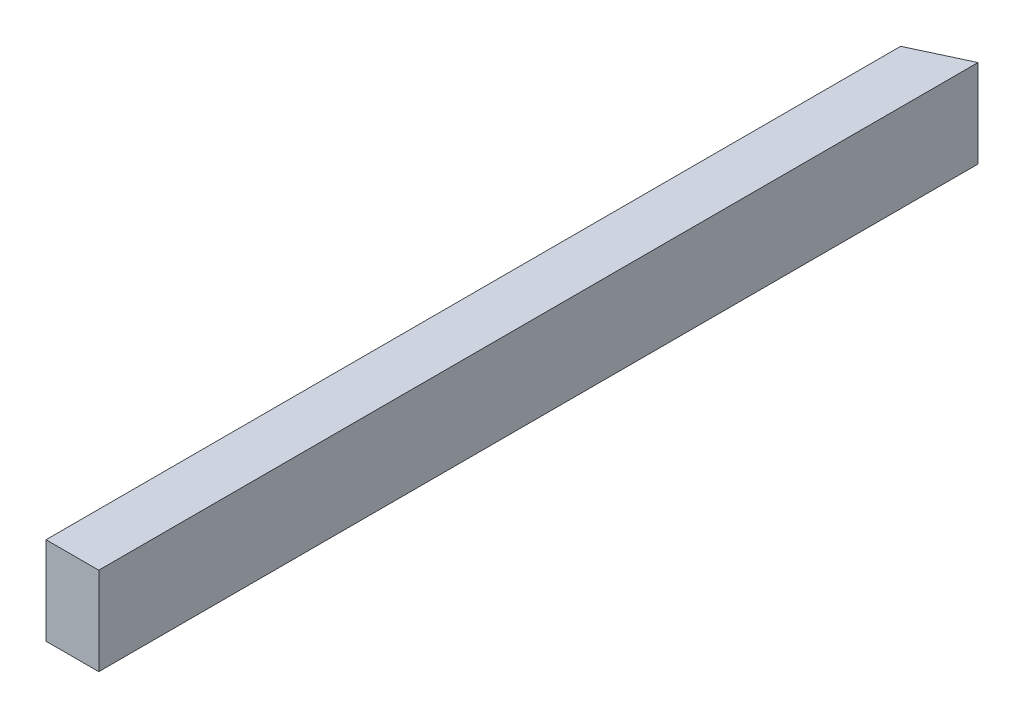
SolidWorks part; units mm, degrees
ref_plane "Front Plane" through (0, 0, 0) normal (0, 0, 1) x (1, 0, 0)
ref_plane "Top Plane" through (0, 0, 0) normal (0, 1, 0) x (1, 0, 0)
ref_plane "Right Plane" through (0, 0, 0) normal (1, 0, 0) x (0, 0, -1)
sketch "Sketch1" plane through (0, 0, 0) normal (0, 1, 0) x (1, 0, 0)
  line L0 (-25.8587, 19.0368) -> (-28.8587, 17.6378)
  line L2 (-28.8587, 17.6378) -> (-28.8587, -30.9632)
  line L3 (-28.8587, -30.9632) -> (-25.8587, -30.9632)
  line L4 (-25.8587, 19.0368) -> (-25.8587, -30.9632)
  line L5 (-25.8587, 19.0368) -> (-28.8587, 19.0368) construction
  line L6 (-28.8587, 19.0368) -> (-28.8587, 17.6378) construction
  dimension "D1" = 3
  dimension "D2" = 50
  dimension "D3" = 25
extrude "Boss-Extrude1" add sketch "Sketch1" along normal blind 5
